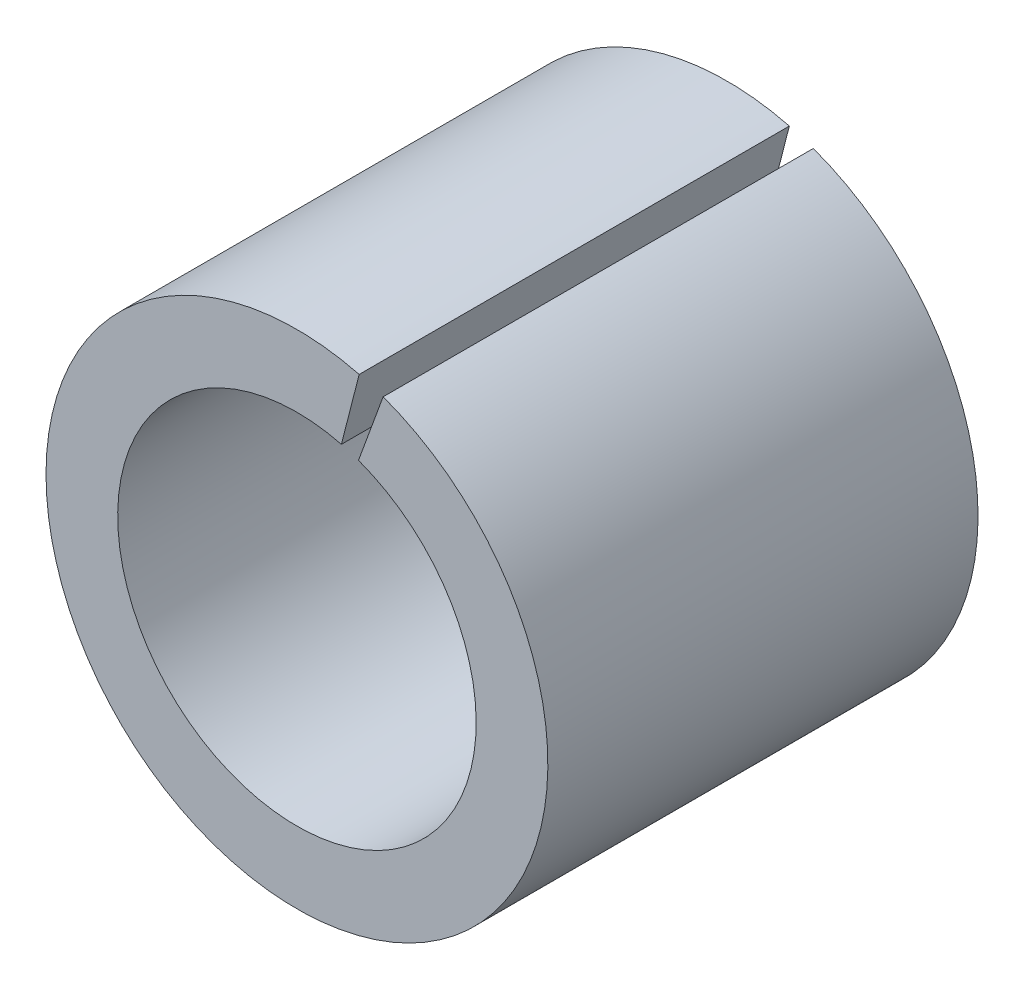
SolidWorks part; units mm, degrees
ref_plane "前视基准面" through (0, 0, 0) normal (0, 0, 1) x (1, 0, 0)
ref_plane "上视基准面" through (0, 0, 0) normal (0, 1, 0) x (1, 0, 0)
ref_plane "右视基准面" through (0, 0, 0) normal (1, 0, 0) x (0, 0, -1)
sketch "草图1" plane through (0, 0, 0) normal (0, 0, 1) x (1, 0, 0)
  circle A0 centre (0, 0) radius 3.5
  circle A1 centre (0, 0) radius 2.5
  dimension "D1" = 5
  dimension "D2" = 7
extrude "凸台-拉伸1" add sketch "草图1" along normal blind 6
sketch "草图2" plane through (0, 0, 6) normal (0, 0, 1) x (1, 0, 0)
  line L0 (0, 0) -> (1.1956, 4.6702)
  line L1 (1.1956, 4.6702) -> (1.7082, 4.6702)
  line L2 (1.7082, 4.6702) -> (0, 0)
extrude "切除-拉伸1" cut sketch "草图2" against normal blind 6
